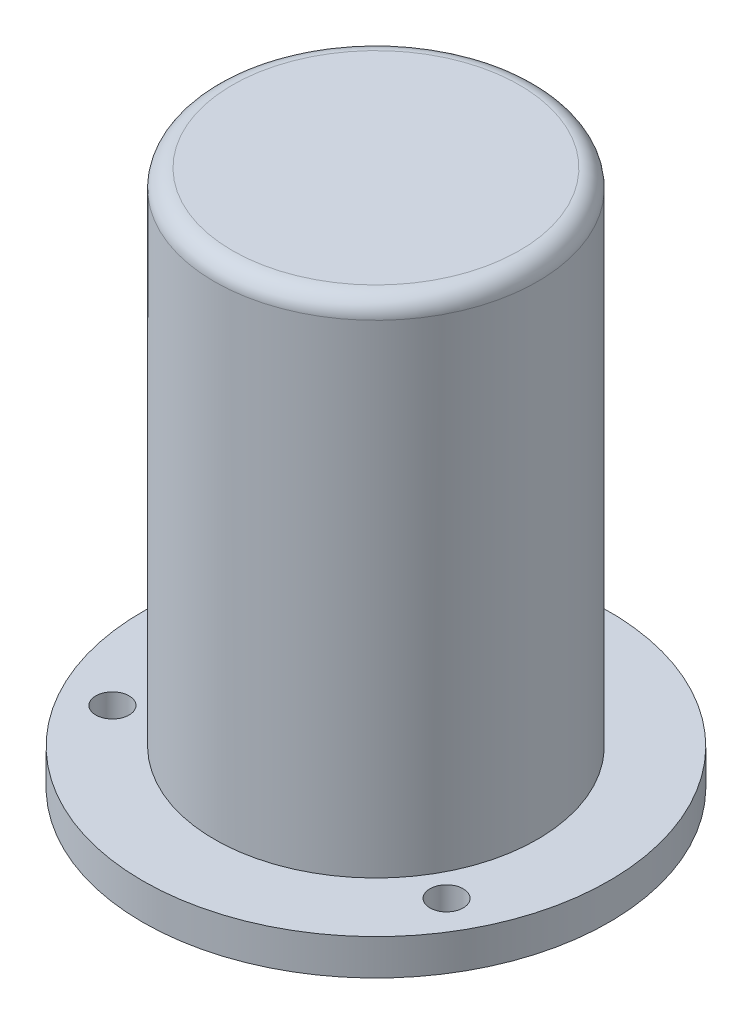
SolidWorks part; units mm, degrees
material "AISI 304"
ref_plane "Front Plane" through (0, 0, 0) normal (0, 0, 1) x (1, 0, 0)
ref_plane "Top Plane" through (0, 0, 0) normal (0, 1, 0) x (1, 0, 0)
ref_plane "Right Plane" through (0, 0, 0) normal (1, 0, 0) x (0, 0, -1)
sketch "Sketch1" plane through (0, 0, 0) normal (0, 1, 0) x (1, 0, 0)
  circle A0 centre (0, 0) radius 20.6375
  dimension "D1" = 41.275
extrude "Boss-Extrude1" add sketch "Sketch1" along normal blind 3.175
sketch "Sketch2" plane through (0, 3.175, 0) normal (0, 1, 0) x (1, 0, 0)
  circle A0 centre (0, 0) radius 14.2875
  dimension "D1" = 28.575
extrude "Boss-Extrude2" add sketch "Sketch2" along normal blind 47.498 from surface at -3.175 starting at face at (0, 0, 20.6375)
sketch "Sketch3" plane through (0, 3.175, 0) normal (0, 1, 0) x (1, 0, 0)
  circle A0 centre (0, 17.0688) radius 1.4732
  circle A1 centre (14.782, -8.5344) radius 1.4732
  circle A2 centre (-14.782, -8.5344) radius 1.4732
  circle A3 centre (0, 0) radius 17.0688 construction
  dimension "D1" = 2.9464
  dimension "D2" = 17.0688
  dimension "D3" = 3
extrude "Cut-Extrude1" cut sketch "Sketch3" against normal through all
sketch "Sketch4" plane through (0, 0, 0) normal (0, -1, 0) x (1, 0, 0)
  circle A0 centre (0, 0) radius 13.6144
  dimension "D1" = 27.2288
extrude "Cut-Extrude2" cut sketch "Sketch4" against normal offset from surface (46.8122 mm away) 0.6858 up to face at (0, 47.498, 14.2875)
fillet "Fillet1" radius 1.5875 1 edges at (0, 47.498, 14.2875)
